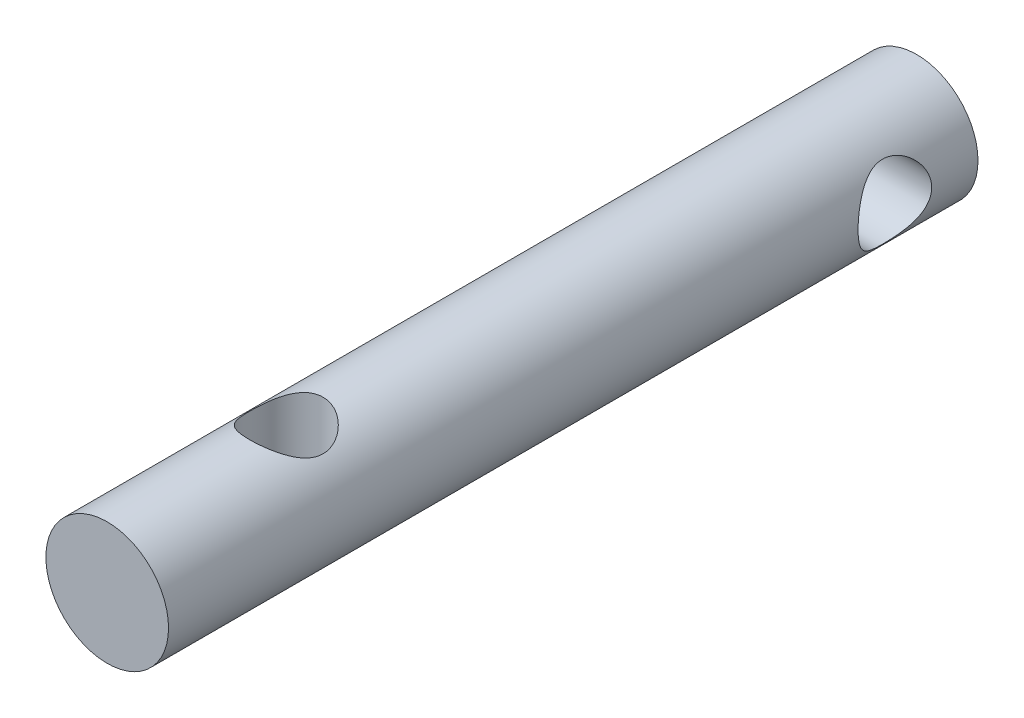
SolidWorks part; units mm, degrees
ref_plane "Front Plane" through (0, 0, 0) normal (0, 0, 1) x (1, 0, 0)
ref_plane "Top Plane" through (0, 0, 0) normal (0, 1, 0) x (1, 0, 0)
ref_plane "Right Plane" through (0, 0, 0) normal (1, 0, 0) x (0, 0, -1)
sketch "Sketch1" plane through (0, 0, 0) normal (0, 0, 1) x (1, 0, 0)
  circle A0 centre (0, 0) radius 3.175
  dimension "D1" = 6.35
extrude "Boss-Extrude1" add sketch "Sketch1" along normal blind 41.91 contours A0
sketch "Sketch2" plane through (0, 0, 0) normal (0, 1, 0) x (1, 0, 0)
  line L0 (-3.175, -41.91) -> (3.175, -41.91) construction
  line L1 (0, -41.91) -> (0, 0) construction
  circle A0 centre (0, -32.639) radius 1.905
  point P4 (0, 0)
  dimension "D2" = 3.81
  dimension "D1" = 9.271
extrude "Cut-Extrude1" cut sketch "Sketch2" against normal through all and the other way through all
sketch "Sketch3" plane through (0, 0, 0) normal (1, 0, 0) x (0, 0, -1)
  circle A0 centre (-4.3031, 0) radius 1.905
  point P2 (0, 0)
  dimension "D2" = 3.81
  dimension "D1" = 4.3031
extrude "Cut-Extrude2" cut sketch "Sketch3" against normal through all and the other way through all
